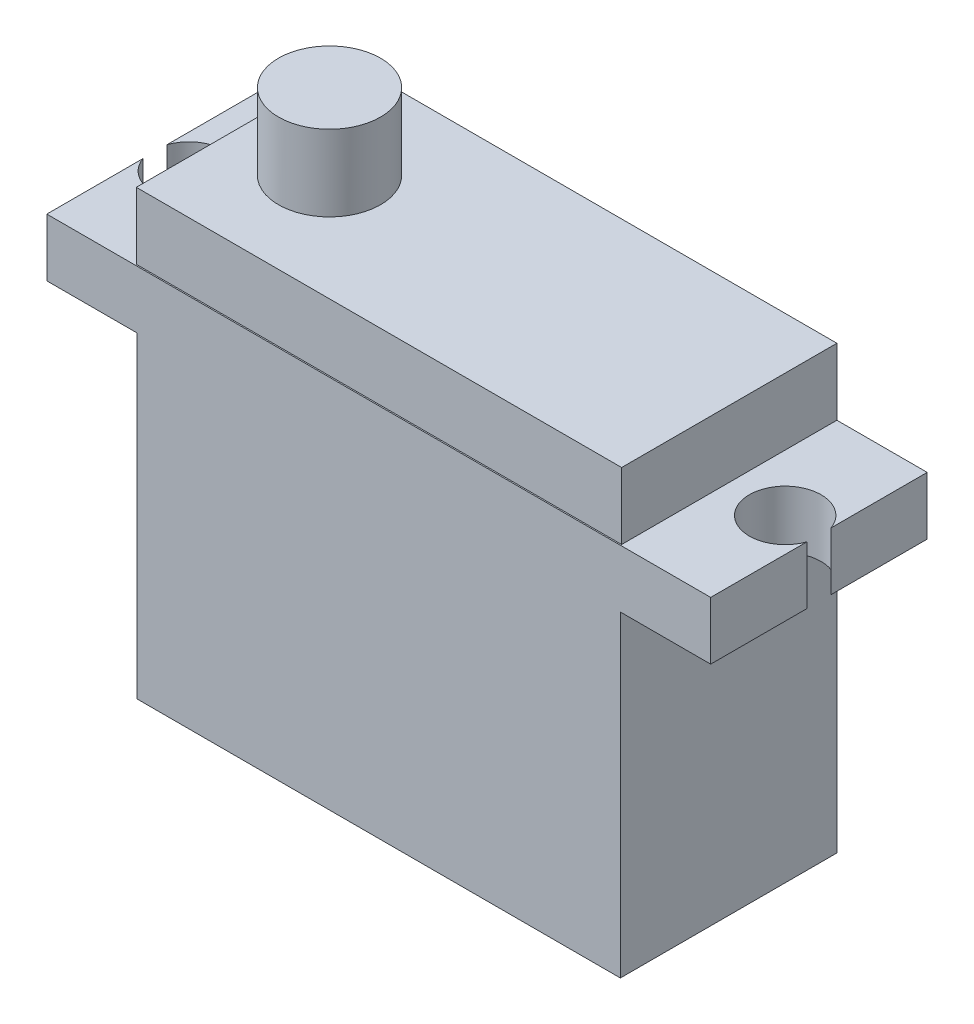
SolidWorks part; units mm, degrees
ref_plane "Front Plane" through (0, 0, 0) normal (0, 0, 1) x (1, 0, 0)
ref_plane "Top Plane" through (0, 0, 0) normal (0, 1, 0) x (1, 0, 0)
ref_plane "Right Plane" through (0, 0, 0) normal (1, 0, 0) x (0, 0, -1)
sketch "Sketch1" plane through (0, 0, 0) normal (0, 1, 0) x (1, 0, 0)
  line L1 (-14.5415, -6.5151) -> (14.5415, -6.5151)
  line L2 (-14.5415, -6.5151) -> (-14.5415, 6.5151)
  line L3 (-14.5415, 6.5151) -> (14.5415, 6.5151)
  line L4 (14.5415, -6.5151) -> (14.5415, 6.5151)
  line L5 (-14.5415, -6.5151) -> (14.5415, 6.5151) construction
  line L6 (-14.5415, 6.5151) -> (14.5415, -6.5151) construction
  point P0 (0, 0)
  dimension "D1" = 13.0302
  dimension "D2" = 29.083
extrude "Boss-Extrude1" add sketch "Sketch1" along normal blind 19.0754
sketch "Sketch2" plane through (0, 19.0754, 0) normal (0, 1, 0) x (1, 0, 0)
  line L1 (-19.9771, -6.5151) -> (19.9771, -6.5151)
  line L2 (-19.9771, -6.5151) -> (-19.9771, 6.5151)
  line L3 (-19.9771, 6.5151) -> (19.9771, 6.5151)
  line L4 (19.9771, -6.5151) -> (19.9771, 6.5151)
  line L5 (-19.9771, -6.5151) -> (19.9771, 6.5151) construction
  line L6 (-19.9771, 6.5151) -> (19.9771, -6.5151) construction
  point P0 (0, 0)
  dimension "D1" = 13.0302
  dimension "D2" = 39.9542
extrude "Boss-Extrude2" add sketch "Sketch2" along normal blind 3.4798
sketch "Sketch3" plane through (0, 22.5552, 0) normal (0, 1, 0) x (1, 0, 0)
  line L0 (19.9771, 6.5151) -> (-19.9771, 6.5151) construction
  line L1 (-14.6685, -6.4389) -> (14.5415, -6.4389)
  line L2 (-14.6685, -6.4389) -> (-14.6685, 6.5151)
  line L3 (-14.6685, 6.5151) -> (14.5415, 6.5151)
  line L4 (14.5415, -6.4389) -> (14.5415, 6.5151)
  line L5 (-14.6685, -6.4389) -> (14.5415, 6.5151) construction
  line L6 (-14.6685, 6.5151) -> (14.5415, -6.4389) construction
  line L7 (14.5415, -6.5151) -> (14.5415, 6.5151) construction
  point P0 (-0.0635, 0.0381)
  dimension "D1" = 12.954
  dimension "D2" = 29.21
  dimension "D3" = 0
extrude "Boss-Extrude3" add sketch "Sketch3" along normal blind 4.0132
sketch "Sketch4" plane through (0, 26.5684, 0) normal (0, 1, 0) x (1, 0, 0)
  line L0 (-19.9771, 6.5151) -> (-19.9771, -6.5151) construction
  circle A0 centre (-9.4771, 0) radius 3.0711
  dimension "D1" = 10.5
extrude "Boss-Extrude4" add sketch "Sketch4" along normal blind 4.572
sketch "Sketch5" plane through (0, 22.5552, 0) normal (0, 1, 0) x (1, 0, 0)
  line L0 (-19.9771, 6.5151) -> (-19.9771, -6.5151) construction
  line L1 (19.9771, -6.5151) -> (19.9771, 6.5151) construction
  circle A0 centre (-17.9451, 0) radius 2.159
  circle A1 centre (17.9451, 0) radius 2.159
  dimension "D1" = 4.318
  dimension "D3" = 4.318
  dimension "D2" = 2.032
  dimension "D4" = 2.032
extrude "Cut-Extrude1" cut sketch "Sketch5" against normal up to surface (3.4798 mm away) up to face at (-17.2593, 19.0754, 0)
